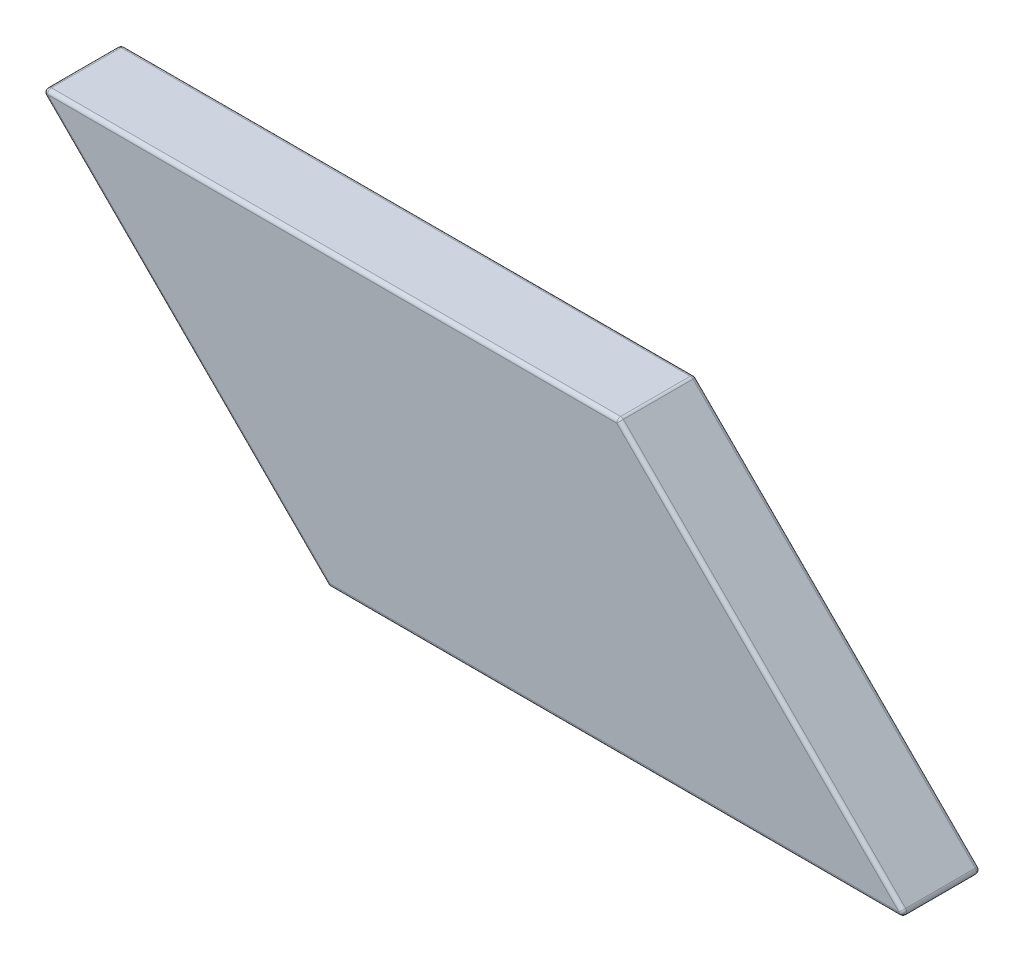
SolidWorks part; units mm, degrees
ref_plane "前视基准面" through (0, 0, 0) normal (0, 0, 1) x (1, 0, 0)
ref_plane "上视基准面" through (0, 0, 0) normal (0, 1, 0) x (1, 0, 0)
ref_plane "右视基准面" through (0, 0, 0) normal (1, 0, 0) x (0, 0, -1)
sketch "草图1" plane through (0, 0, 0) normal (0, 0, 1) x (1, 0, 0)
  line L27 (-37.5, 37.5) -> (37.5, 37.5)
  line L28 (0, 0) -> (-37.5, 37.5)
  line L29 (37.5, 37.5) -> (75, 0)
  line L30 (0, 0) -> (75, 0)
  line L31 (37.5, 37.5) -> (0, 0) construction
  dimension "D8" = 75
  dimension "D9" = 135
  dimension "D10" = 45
extrude "凸台-拉伸1" add sketch "草图1" along normal blind 10
fillet "圆角1" radius 0.5 12 edges at (56.25, 18.75, 0) (0, 37.5, 0) (37.5, 0, 10) (56.25, 18.75, 10) (0, 37.5, 10) (-18.75, 18.75, 10) (-37.5, 37.5, 5) (37.5, 37.5, 5) (75, 0, 5) (-18.75, 18.75, 0) (0, 0, 5) (37.5, 0, 0)
